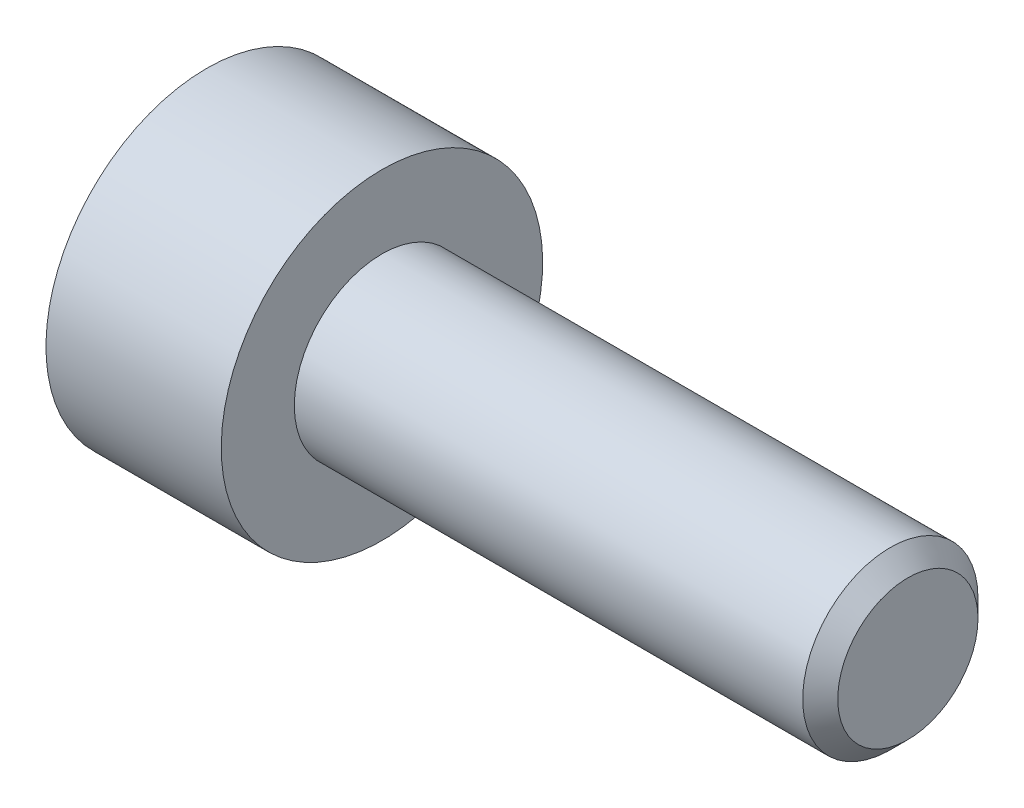
SolidWorks part; units mm, degrees
material "Plain Carbon Steel"
ref_plane "Front Plane" through (0, 0, 0) normal (0, 0, 1) x (1, 0, 0)
ref_plane "Top Plane" through (0, 0, 0) normal (0, 1, 0) x (1, 0, 0)
ref_plane "Right Plane" through (0, 0, 0) normal (1, 0, 0) x (0, 0, -1)
sketch "Sketch2" plane through (0, 0, 0) normal (1, 0, 0) x (0, 0, -1)
  circle A0 centre (0, 0) radius 1.5
  dimension "D1" = 3
extrude "Boss-Extrude1" add sketch "Sketch2" against normal blind 9
chamfer "Chamfer1" distance 0.3 angle 45 1 edges at (0, 0, -1.5)
sketch "Sketch6" plane through (0, 0, 0) normal (0, 0, 1) x (1, 0, 0)
  line L0 (-12, 0) -> (-12, 2.75)
  line L1 (-12, 0) -> (-9, 0)
  line L2 (-12, 2.75) -> (-9, 2.75)
  line L6 (-9, 2.75) -> (-9, 0)
  line L8 (-9, 0) -> (-14.6471, 0) construction
  line L10 (-9, 1.5) -> (-9, -1.5) construction
  dimension "D1" = 3
  dimension "D2" = 5.5
revolve "Revolve1" add sketch "Sketch6" angle 360 about L8
sketch "Sketch7" plane through (-12, 0, 0) normal (-1, 0, 0) x (0, 0, 1)
  line L1 (0, 1.4434) -> (-1.25, 0.7217)
  line L2 (-1.25, 0.7217) -> (-1.25, -0.7217)
  line L3 (-1.25, -0.7217) -> (0, -1.4434)
  line L4 (0, -1.4434) -> (1.25, -0.7217)
  line L5 (1.25, -0.7217) -> (1.25, 0.7217)
  line L6 (1.25, 0.7217) -> (0, 1.4434)
  circle A0 centre (0, 0) radius 1.25 construction
  dimension "D1" = 2.5
extrude "Cut-Extrude1" cut sketch "Sketch7" against normal blind 1.6
sketch "Sketch8" plane through (-12, 0, 0) normal (-1, 0, 0) x (0, 0, 1)
  circle A0 centre (0, 0) radius 1.4934
  dimension "D1" = 0.05
extrude "Cut-Extrude2" cut sketch "Sketch8" against normal blind 1 draft 45
